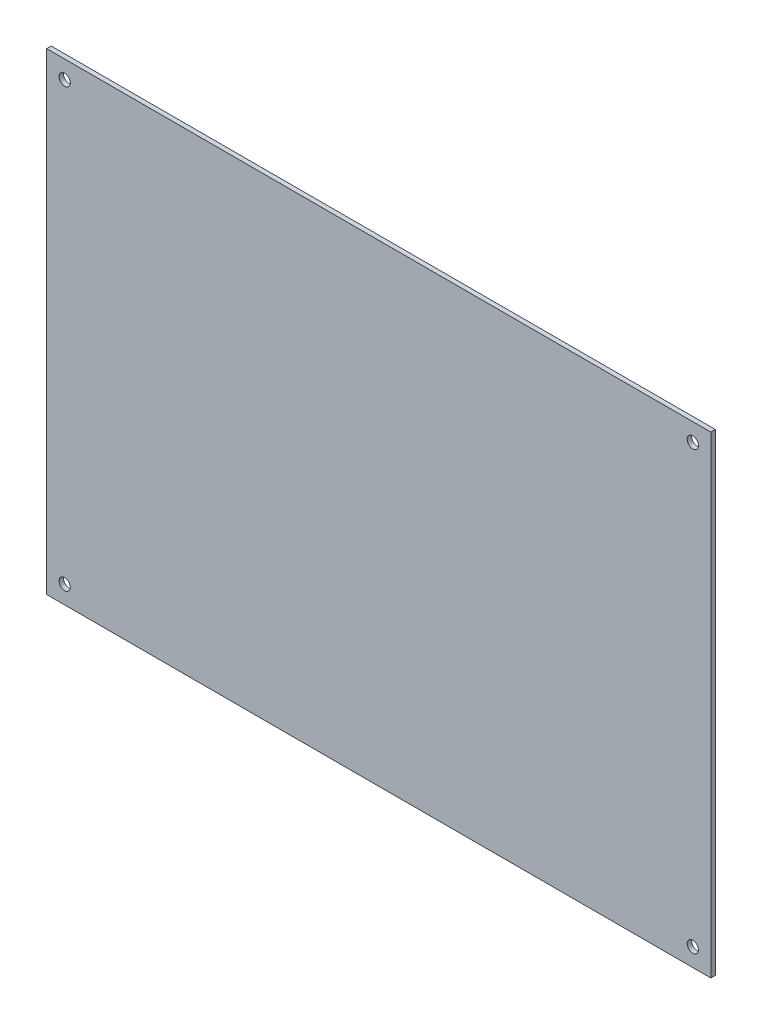
SolidWorks part; units mm, degrees
ref_plane "Front Plane" through (0, 0, 0) normal (0, 0, 1) x (1, 0, 0)
ref_plane "Top Plane" through (0, 0, 0) normal (0, 1, 0) x (1, 0, 0)
ref_plane "Right Plane" through (0, 0, 0) normal (1, 0, 0) x (0, 0, -1)
sketch "Sketch2" plane through (0, 0, 0) normal (0, 0, 1) x (1, 0, 0)
  line L1 (147.5, 105) -> (-147.5, 105)
  line L2 (147.5, 105) -> (147.5, -105)
  line L3 (147.5, -105) -> (-147.5, -105)
  line L4 (-147.5, 105) -> (-147.5, -105)
  line L5 (147.5, 105) -> (-147.5, -105) construction
  line L6 (147.5, -105) -> (-147.5, 105) construction
  point P4 (0, 0)
  dimension "D1" = 210
  dimension "D2" = 295
extrude "Boss-Extrude1" add sketch "Sketch2" along normal blind 2
sketch "Sketch3" plane through (0, 0, 2) normal (0, 0, 1) x (1, 0, 0)
  line L0 (147.5, 2.1564) -> (-147.5, 2.1564) construction
  line L1 (147.5, -105) -> (147.5, 105) construction
  line L2 (-147.5, 105) -> (-147.5, -105) construction
  line L3 (2.6185, 105) -> (2.6185, -105) construction
  line L4 (147.5, 105) -> (-147.5, 105) construction
  line L5 (-147.5, -105) -> (147.5, -105) construction
  line L7 (-147.5, 105) -> (-139.5, 105) construction
  line L8 (-147.5, 105) -> (-147.5, 97) construction
  line L9 (-147.5, 97) -> (-139.5, 97) construction
  line L10 (-139.5, 105) -> (-139.5, 97) construction
  line L11 (-147.5, 105) -> (-139.5, 97) construction
  line L12 (-147.5, 97) -> (-139.5, 105) construction
  circle A0 centre (-139.5, 97) radius 2.5
  point P16 (-143.5, 101)
  dimension "D2" = 5
  dimension "D1" = 8
extrude "Cut-Extrude1" cut sketch "Sketch3" against normal blind 10 contours A0
mirror "Mirror1" about plane through (0, 0, 0) normal (1, 0, 0) of "Cut-Extrude1"
mirror "Mirror2" about plane through (0, 0, 0) normal (0, 1, 0) of "Mirror1", "Cut-Extrude1"
